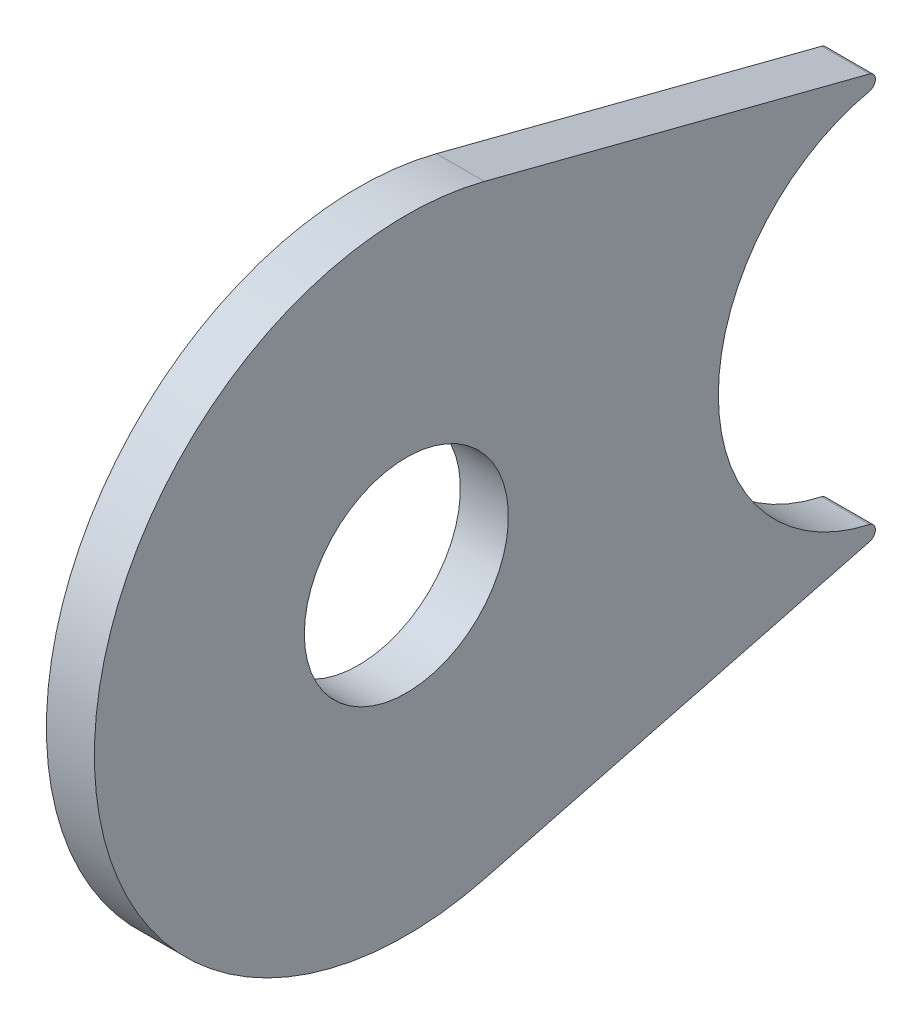
SolidWorks part; units mm, degrees
material "Custom Plastic"
ref_plane "X-Y Datum" through (0, 0, 0) normal (0, 0, 1) x (1, 0, 0)
ref_plane "X-Z Datum" through (0, 0, 0) normal (0, 1, 0) x (1, 0, 0)
ref_plane "Y-Z Datum" through (0, 0, 0) normal (1, 0, 0) x (0, 0, -1)
sketch "Sketch1" plane through (0, 0, 0) normal (1, 0, 0) x (0, 0, -1)
  line L0 (33.3375, -12.7) -> (5.1638, -19.981)
  line L1 (33.3375, 12.7) -> (5.1638, 19.981)
  arc A0 (5.1638, 19.981) -> (5.1638, -19.981) centre (0, 0) ccw
  circle A1 centre (0, 0) radius 6.75
  arc A4 (33.3375, -12.7) -> (33.3375, 12.7) centre (33.3375, 0) cw
  circle A5 centre (33.3375, 0) radius 12.7 construction
  dimension "D1" = 41.275
  dimension "D2" = 13.5
  dimension "D3" = 25.4
  dimension "D5" = 13.8875
extrude "Boss-Extrude1" add sketch "Sketch1" along normal mid plane 3.175 contours A1 | L0 A4 L1 A0 A1
fillet "Fillet1" radius 0.508 1 edges at (0, -12.7, -33.3375)
fillet "Fillet2" radius 0.508 1 edges at (0, 12.7, -33.3375)
hole_wizard "M12 Clearance Hole1" positions "Sketch4" profile "Sketch5" hole size "M12" standard "ANSI Metric" end condition through all
sketch "Sketch4" plane through (-1.5875, 0, 0) normal (-1, 0, 0) x (0, 0, 1)
  point P0 (0, 0)
sketch "Sketch5" plane through (-1.5875, 0, 0) normal (0, 1, 0) x (0, 0, 1)
  line L0 (0, 0) -> (0, 3.175)
  line L1 (0, 3.175) -> (6.75, 3.175)
  line L2 (6.75, 3.175) -> (6.75, 0)
  line L5 (6.75, 0) -> (0, 0)
  line L11 (0, -6.35) -> (0, 107.95) construction
  dimension "Thru Hole Dia." = 13.5
  dimension "Thru Hole Depth" = 3.175
